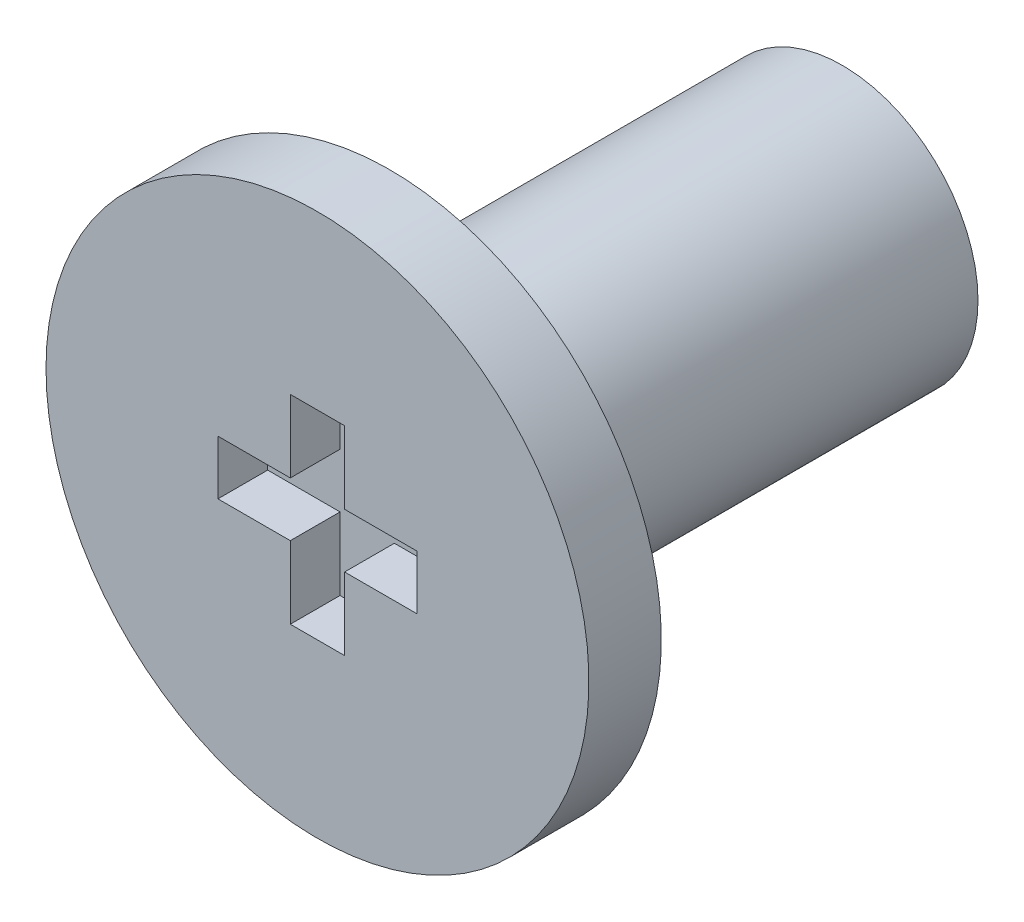
SolidWorks part; units mm, degrees
ref_plane "前视基准面" through (0, 0, 0) normal (0, 0, 1) x (1, 0, 0)
ref_plane "上视基准面" through (0, 0, 0) normal (0, 1, 0) x (1, 0, 0)
ref_plane "右视基准面" through (0, 0, 0) normal (1, 0, 0) x (0, 0, -1)
other "Configuration Table"
sketch "草图1" plane through (0, 0, 0) normal (0, 0, 1) x (1, 0, 0)
  circle A0 centre (0, 0) radius 1.5
extrude "标准杆径_头下长度" add sketch "草图1" against normal blind 5
sketch "草图2" plane through (0, 0, 0) normal (0, 0, 1) x (1, 0, 0)
  circle A0 centre (0, 0) radius 2.75
sketch "草图4" plane through (0, 0, 0) normal (0, 1, 0) x (1, 0, 0)
  line L0 (0, 0) -> (3.45, 0)
  line L1 (3.45, 0) -> (3.45, -0.3426)
  line L2 (0, -1.9) -> (0, 0)
  line L3 (0, 2) -> (0, -3.9) construction
  arc A0 (3.45, -0.3426) -> (0, -1.9) centre (0, 2.7) cw
sketch "草图5" plane through (0, 0, 0) normal (0, 0, 1) x (1, 0, 0)
  line L0 (-0.3, -1.45) -> (0.3, -1.45)
  line L1 (0.3, -1.45) -> (0.3, -0.3)
  line L2 (0.3, -0.3) -> (1.45, -0.3)
  line L3 (1.45, -0.3) -> (1.45, 0.3)
  line L4 (1.45, 0.3) -> (0.3, 0.3)
  line L5 (0.3, 0.3) -> (0.3, 1.45)
  line L6 (0.3, 1.45) -> (-0.3, 1.45)
  line L7 (-0.3, 1.45) -> (-0.3, 0.3)
  line L8 (-0.3, 0.3) -> (-1.45, 0.3)
  line L9 (-1.45, 0.3) -> (-1.45, -0.3)
  line L10 (-1.45, -0.3) -> (-0.3, -0.3)
  line L11 (-0.3, -0.3) -> (-0.3, -1.45)
sketch "草图6" plane through (0, 0, 0) normal (0, 1, 0) x (1, 0, 0)
  line L0 (0, 0) -> (3, 0)
  line L1 (3, 0) -> (3, -0.8)
  line L2 (3, -0.8) -> (0, -0.8)
  line L3 (0, -0.8) -> (0, 0)
  line L4 (0, 2) -> (0, -2.8) construction
revolve "已确认_十字槽超薄头" add sketch "草图6" angle 360 about L4
sketch "草图7" plane through (0, 0, 0) normal (0, 0, 1) x (1, 0, 0)
  line L0 (-0.3, -1.1) -> (0.3, -1.1)
  line L1 (0.3, -1.1) -> (0.3, -0.3)
  line L2 (0.3, -0.3) -> (1.1, -0.3)
  line L3 (1.1, -0.3) -> (1.1, 0.3)
  line L4 (1.1, 0.3) -> (0.3, 0.3)
  line L5 (0.3, 0.3) -> (0.3, 1.1)
  line L6 (0.3, 1.1) -> (-0.3, 1.1)
  line L7 (-0.3, 1.1) -> (-0.3, 0.3)
  line L8 (-0.3, 0.3) -> (-1.1, 0.3)
  line L9 (-1.1, 0.3) -> (-1.1, -0.3)
  line L10 (-1.1, -0.3) -> (-0.3, -0.3)
  line L11 (-0.3, -0.3) -> (-0.3, -1.1)
extrude "十字槽_PH1_简化" cut sketch "草图7" against normal blind 0.56 from offset 0.81
